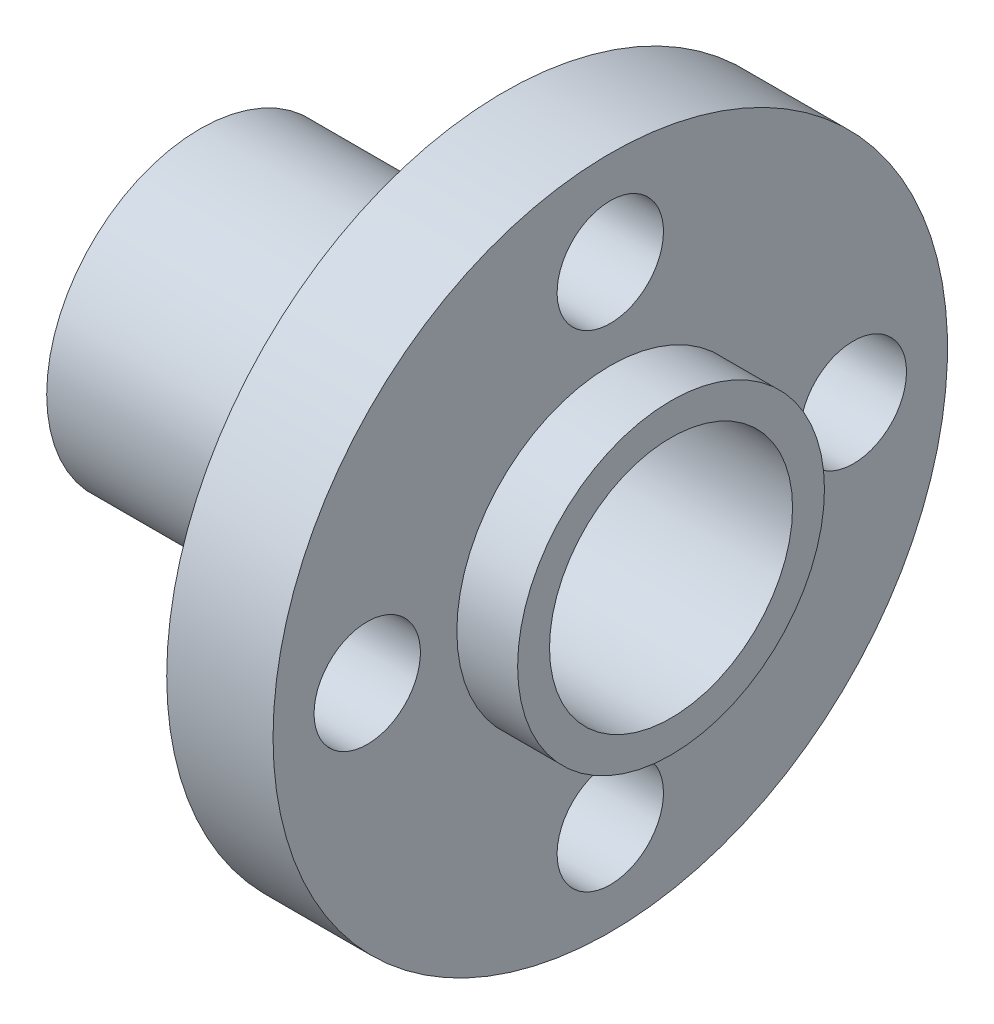
SolidWorks part; units mm, degrees
material "Brass"
ref_plane "Front Plane" through (0, 0, 0) normal (0, 0, 1) x (1, 0, 0)
ref_plane "Top Plane" through (0, 0, 0) normal (0, 1, 0) x (1, 0, 0)
ref_plane "Right Plane" through (0, 0, 0) normal (1, 0, 0) x (0, 0, -1)
sketch "Sketch1" plane through (0, 0, 0) normal (0, 0, 1) x (1, 0, 0)
  line L0 (0, 0) -> (18.7178, 0) construction
  line L1 (0, 0) -> (0, 4) construction
  line L2 (0, 4) -> (15.5, 4)
  line L3 (15.5, 4) -> (15.5, 5.05)
  line L4 (15.5, 5.05) -> (0, 5.05)
  line L5 (0, 5.05) -> (0, 4)
  line L7 (10, 11.1) -> (13.5, 11.1)
  line L8 (10, 11.1) -> (10, 5.05)
  line L10 (13.5, 11.1) -> (13.5, 5.05)
  line L11 (10, 11.1) -> (11.75, 5.05) construction
  line L12 (11.75, 5.05) -> (13.5, 11.1) construction
  point P4 (11.75, 5.05)
  dimension "D1" = 3.5
  dimension "D2" = 15.5
  dimension "D3" = 2
  dimension "D4" = 8
  dimension "D5" = 10.1
  dimension "D6" = 22.2
revolve "Revolve1" add sketch "Sketch1" angle 360 about L0
sketch "Sketch2" plane through (0, 0, 0) normal (1, 0, 0) x (0, 0, -1)
  line L0 (0, 0) -> (8, 0) construction
  circle A0 centre (8, 0) radius 1.75
  dimension "D1" = 3.5
  dimension "D2" = 8
extrude "Cut-Extrude1" cut sketch "Sketch2" along normal through all
pattern_circular "CirPattern1" count 4 over 360 about axis through (0, 0, 0) along (1, 0, 0) of "Cut-Extrude1"
